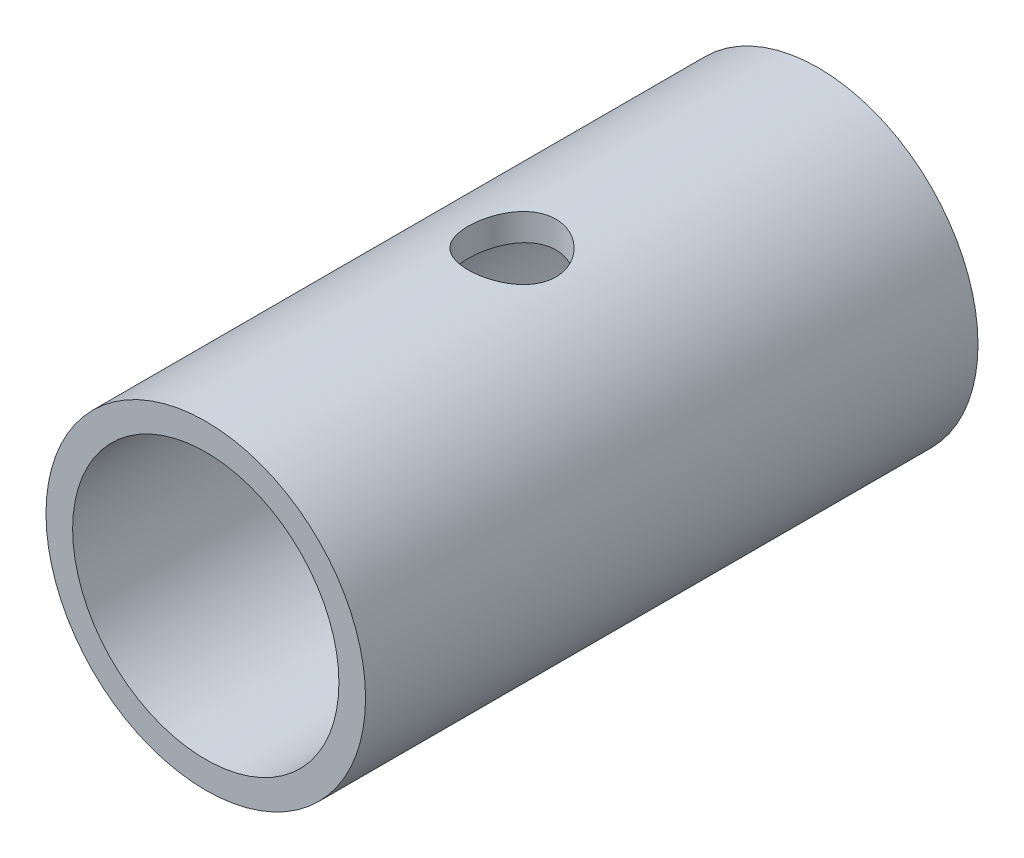
SolidWorks part; units mm, degrees
ref_plane "Front Plane" through (0, 0, 0) normal (0, 0, 1) x (1, 0, 0)
ref_plane "Top Plane" through (0, 0, 0) normal (0, 1, 0) x (1, 0, 0)
ref_plane "Right Plane" through (0, 0, 0) normal (1, 0, 0) x (0, 0, -1)
sketch "Sketch1" plane through (0, 0, 0) normal (0, 0, 1) x (1, 0, 0)
  circle A0 centre (0, 0) radius 6
  circle A1 centre (0, 0) radius 5
  dimension "D1" = 12
  dimension "D2" = 10
extrude "Boss-Extrude2" add sketch "Sketch1" along normal mid plane 23
ref_plane "Plane1" through (0, 6, 0) normal (0, 1, 0) x (1, 0, 0)
sketch "Sketch2" plane through (0, 6, 0) normal (0, 1, 0) x (1, 0, 0)
  circle A0 centre (0, 0) radius 1.65
  point P0 (0, 0)
  dimension "D1" = 3.3
extrude "Cut-Extrude1" cut sketch "Sketch2" against normal up to next
cosmetic thread "Cosmetic Thread1" parameters "D2"=4
